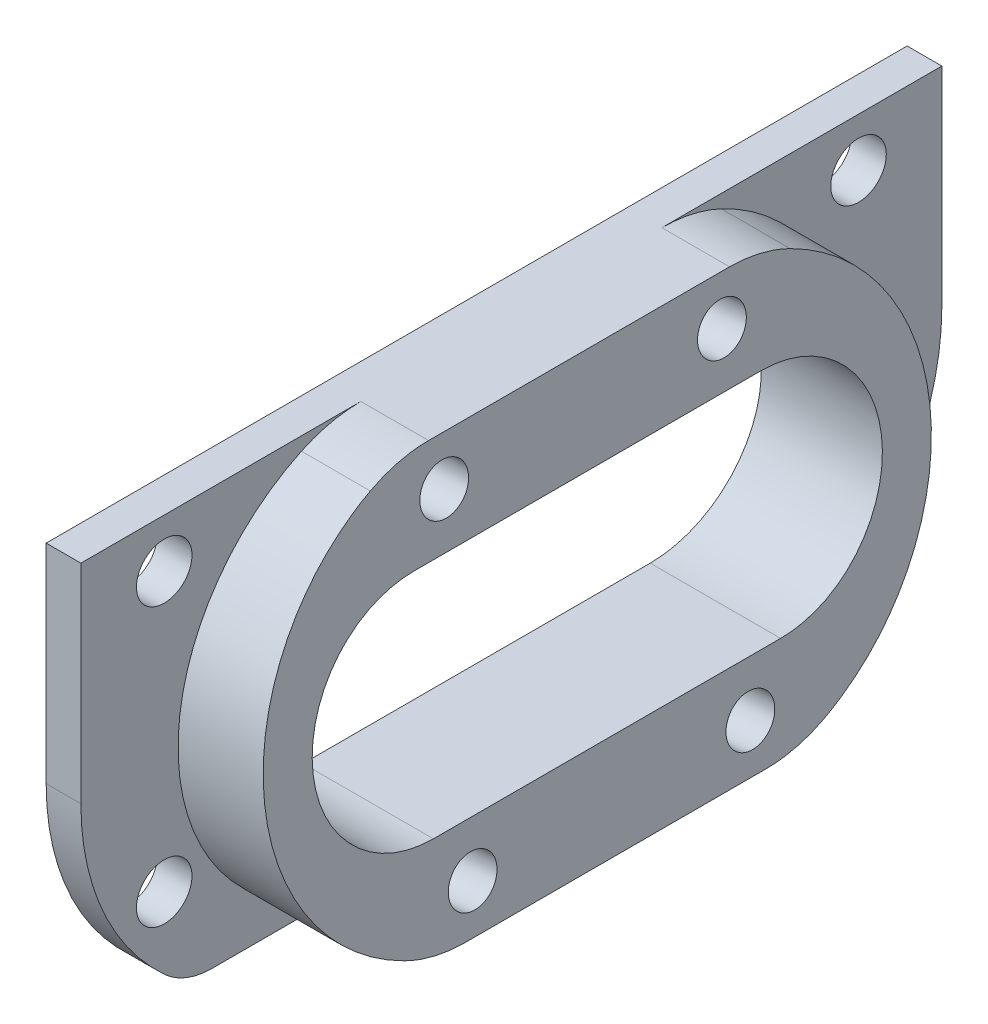
SolidWorks part; units mm, degrees
ref_plane "Płaszczyzna przednia" through (0, 0, 0) normal (0, 0, 1) x (1, 0, 0)
ref_plane "Płaszczyzna górna" through (0, 0, 0) normal (0, 1, 0) x (1, 0, 0)
ref_plane "Płaszczyzna prawa" through (0, 0, 0) normal (1, 0, 0) x (0, 0, -1)
sketch "Szkic1" plane through (0, 0, 0) normal (1, 0, 0) x (0, 0, -1)
  line L0 (-25, -16) -> (25, -16)
  line L1 (25, 16) -> (-25, 16)
  line L2 (-43.1384, -30) -> (43.1384, -30)
  line L3 (-62, 0) -> (62, 0) construction
  line L4 (-62, 30) -> (62, 30)
  line L5 (62, 0) -> (62, 30)
  line L6 (-62, 30) -> (-62, 0)
  line L7 (0, 0) -> (0, 30) construction
  arc A0 (-25, 16) -> (-25, -16) centre (-25, 0) ccw
  arc A1 (25, -16) -> (25, 16) centre (25, 0) ccw
  arc A2 (43.1384, -30) -> (49.8563, -27.4074) centre (43.1384, -20) ccw
  arc A3 (-49.8563, -27.4074) -> (-43.1384, -30) centre (-43.1384, -20) ccw
  arc A6 (49.8563, -27.4074) -> (62, 0) centre (25, 0) ccw
  arc A7 (-62, 0) -> (-49.8563, -27.4074) centre (-25, 0) ccw
  circle A8 centre (-50, 23) radius 4
  circle A9 centre (50, 23) radius 4
  circle A10 centre (50, -17) radius 4
  circle A11 centre (-50, -17) radius 4
  dimension "D2" = 16
  dimension "D3" = 10
  dimension "D4" = 7
  dimension "D5" = 37
  dimension "D10" = 8
  dimension "D1" = 50
  dimension "D6" = 43.1384
  dimension "D7" = 50
  dimension "D8" = 2
  dimension "D9" = 2
extrude "Dodanie-wyciągnięcie1" add sketch "Szkic1" along normal blind 20
sketch "Szkic2" plane through (20, 0, 0) normal (1, 0, 0) x (0, 0, -1)
  line L0 (-25, -16) -> (25, -16) construction
  line L1 (25, 16) -> (-25, 16) construction
  line L2 (-25, -16) -> (25, -16)
  line L3 (25, 16) -> (-25, 16)
  line L6 (21.6718, 30) -> (-21.6718, 30)
  line L7 (-21.6718, -30) -> (21.6718, -30)
  line L8 (0, 0) -> (0, 16) construction
  arc A0 (25, -16) -> (25, 16) centre (25, 0) ccw construction
  arc A1 (-25, 16) -> (-25, -16) centre (-25, 0) ccw construction
  arc A2 (25, -16) -> (25, 16) centre (25, 0) ccw
  arc A3 (-25, 16) -> (-25, -16) centre (-25, 0) ccw
  arc A6 (-30.2337, -28.0747) -> (-30.2337, 28.0747) centre (-16.9348, 0) cw
  arc A7 (30.2337, -28.0747) -> (30.2337, 28.0747) centre (16.9348, 0) ccw
  arc A8 (-30.2337, -28.0747) -> (-21.6718, -30) centre (-21.6718, -10) ccw
  arc A9 (21.6718, -30) -> (30.2337, -28.0747) centre (21.6718, -10) ccw
  arc A10 (30.2337, 28.0747) -> (21.6718, 30) centre (21.6718, 10) ccw
  arc A11 (-21.6718, 30) -> (-30.2337, 28.0747) centre (-21.6718, 10) ccw
  point P4 (-25, 0)
  point P5 (-25, 23)
  point P8 (-25, -23)
  point P9 (25, -23)
  point P10 (25, 0)
  point P11 (25, 23)
  point P23 (-25, -30)
  point P26 (25, -30)
  point P29 (25, 30)
  point P32 (-25, 30)
  dimension "D1" = 20
  dimension "D2" = 20
  dimension "D3" = 20
  dimension "D4" = 20
extrude "Wytnij-wyciągnięcie1" cut sketch "Szkic2" against normal blind 15 flip side to cut
sketch "Szkic3" plane through (0, 0, -62) normal (0, 0, -1) x (-1, 0, 0)
  line L0 (-20, -30) -> (-20, 30)
  line L1 (-20, -30) -> (-14.7507, 30)
  line L2 (-5, 30) -> (-20, 30) construction
  line L3 (-14.7507, 30) -> (-20, 30)
  dimension "D1" = 5
extrude "Wytnij-wyciągnięcie2" cut sketch "Szkic3" against normal through all both and the other way through all
sketch "Szkic6" plane through (17.2434, 1.5086, 0) normal (0.9962, 0.0872, 0) x (0, 0, -1)
  line L0 (25, -17.5755) -> (-25, -17.5755) construction
  line L1 (25, -17.5755) -> (-25, -17.5755)
  line L2 (0, 14.5468) -> (0, -18.3539) construction
  line L3 (-41, -1.5144) -> (41, -1.5144) construction
  line L4 (25, 14.5468) -> (-25, 14.5468)
  line L5 (-25, -17.5755) -> (25, -17.5755)
  line L6 (25, 14.5468) -> (-25, 14.5468)
  line L7 (-25, -17.5755) -> (25, -17.5755)
  ellipse E2 centre (-25, -1.5144) end of major axis (-25, 14.5468) minor radius 16 (-25, 14.5468) -> (-25, -17.5755) ccw
  ellipse E3 centre (25, -1.5144) end of major axis (25, 14.5468) minor radius 16 (25, -17.5755) -> (25, 14.5468) ccw
  ellipse E4 centre (-25, -1.5144) end of major axis (-25, 14.5468) minor radius 16 (-25, 14.5468) -> (-25, -17.5755) ccw
  ellipse E5 centre (25, -1.5144) end of major axis (25, 14.5468) minor radius 16 (25, -17.5755) -> (25, 14.5468) ccw
  point P0 (-20, 21.9856)
  point P2 (20, 21.9856)
  point P3 (20, -25.0144)
  point P11 (-20, -25.0144)
  dimension "D2" = 23.5
  dimension "D3" = 2
  dimension "D4" = 20
  dimension "D1" = 0
  dimension "D5" = 2
hole_wizard "Otwór gwintowany M8x1.01" positions "Szkic 3D2" profile "Szkic8" tap size "M8x1.0" standard "ISO"
sketch3d "Szkic 3D2"
  point P0 (15.3272, 23.4106, 20)
  point P3 (15.3272, 23.4106, -20)
  point P6 (19.4235, -23.4106, -20)
  point P9 (19.4235, -23.4106, 20)
sketch "Szkic8" plane through (15.3272, 23.4106, 20) normal (0, 0, 1) x (-0.0872, 0.9962, 0)
  line L0 (0, 0) -> (0, 12)
  line L1 (0, 12) -> (3.5, 9.897)
  line L2 (3.5, 9.897) -> (3.5, 0)
  line L5 (3.5, 0) -> (0, 0)
  line L10 (0, 12) -> (-3.5, 9.897) construction
  line L11 (0, -6.35) -> (0, 107.95) construction
  dimension "Średnica wiertła gwintu" = 7
  dimension "Głębokość otworu gwintowanego" = 12
  dimension "Kąt wiertła" = 118
cosmetic thread "Gwint otworu1" parameters "D1"=9.897, "D2"=8
cosmetic thread "Gwint otworu2" parameters "D1"=9.897, "D2"=8
cosmetic thread "Gwint otworu3" parameters "D1"=9.897, "D2"=8
cosmetic thread "Gwint otworu4" parameters "D1"=9.897, "D2"=8
